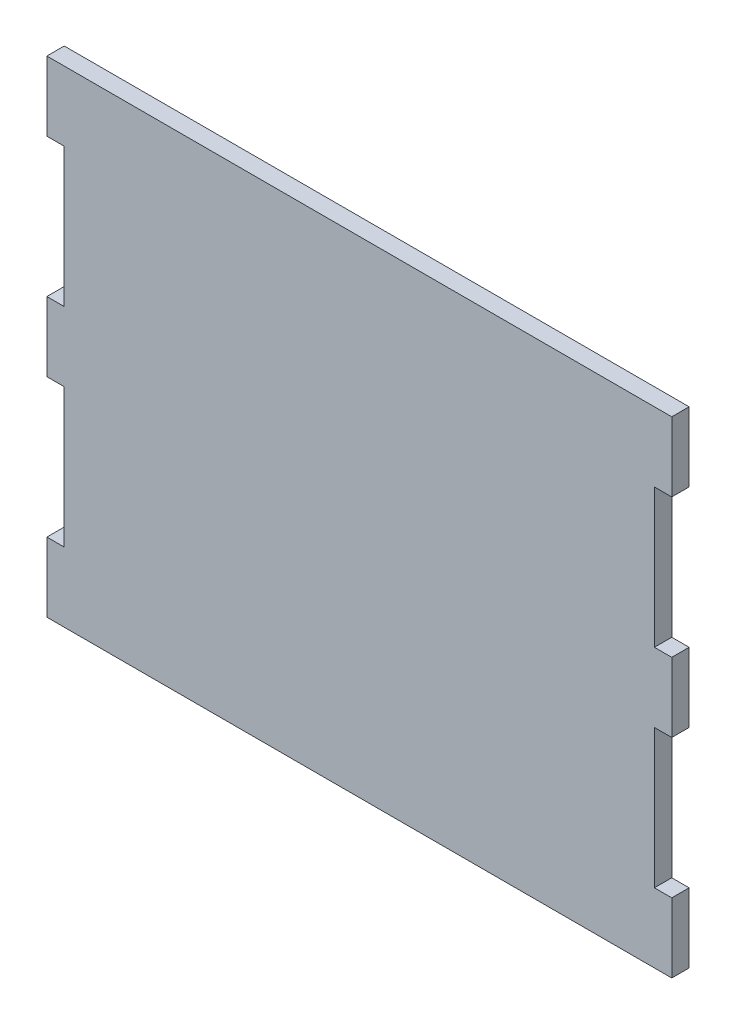
SolidWorks part; units mm, degrees
material "Trupan"
ref_plane "Alzado" through (0, 0, 0) normal (0, 0, 1) x (1, 0, 0)
ref_plane "Planta" through (0, 0, 0) normal (0, 1, 0) x (1, 0, 0)
ref_plane "Vista lateral" through (0, 0, 0) normal (1, 0, 0) x (0, 0, -1)
sketch "Croquis1" plane through (0, 0, 0) normal (0, 0, 1) x (1, 0, 0)
  line L1 (90, -70) -> (-90, -70)
  line L2 (90, -70) -> (90, 70)
  line L3 (90, 70) -> (-90, 70)
  line L4 (-90, -70) -> (-90, 70)
  line L5 (90, -70) -> (-90, 70) construction
  line L6 (90, 70) -> (-90, -70) construction
  point P0 (0, 0)
  dimension "D1" = 180
  dimension "D2" = 140
extrude "Saliente-Extruir1" add sketch "Croquis1" along normal blind 5
sketch "Croquis2" plane through (0, 0, 5) normal (0, 0, 1) x (1, 0, 0)
  line L1 (-90, 70) -> (-82, 70)
  line L2 (-90, 70) -> (-90, 50)
  line L3 (-90, 50) -> (-82, 50)
  line L4 (-82, 70) -> (-82, 50)
  dimension "D1" = 20
  dimension "D2" = 8
sketch "Croquis3" plane through (0, 0, 5) normal (0, 0, 1) x (1, 0, 0)
  line L0 (-90, 70) -> (-90, -70) construction
  line L1 (-90, 10) -> (-85, 10)
  line L2 (-90, 10) -> (-90, -10)
  line L3 (-90, -10) -> (-85, -10)
  line L4 (-85, 10) -> (-85, -10)
  point P6 (-85, 0)
  dimension "D1" = 20
  dimension "D2" = 5
sketch "Croquis4" plane through (0, 0, 5) normal (0, 0, 1) x (1, 0, 0)
  line L1 (-90, 50) -> (-85, 50)
  line L2 (-90, 50) -> (-90, 10)
  line L3 (-90, 10) -> (-85, 10)
  line L4 (-85, 50) -> (-85, 10)
extrude "Cortar-Extruir3" cut sketch "Croquis4" against normal through all
mirror "Simetría4" about plane through (0, 0, 0) normal (0, 1, 0) of "Cortar-Extruir3"
mirror "Simetría5" about plane through (0, 0, 0) normal (1, 0, 0) of "Simetría4", "Cortar-Extruir3"
